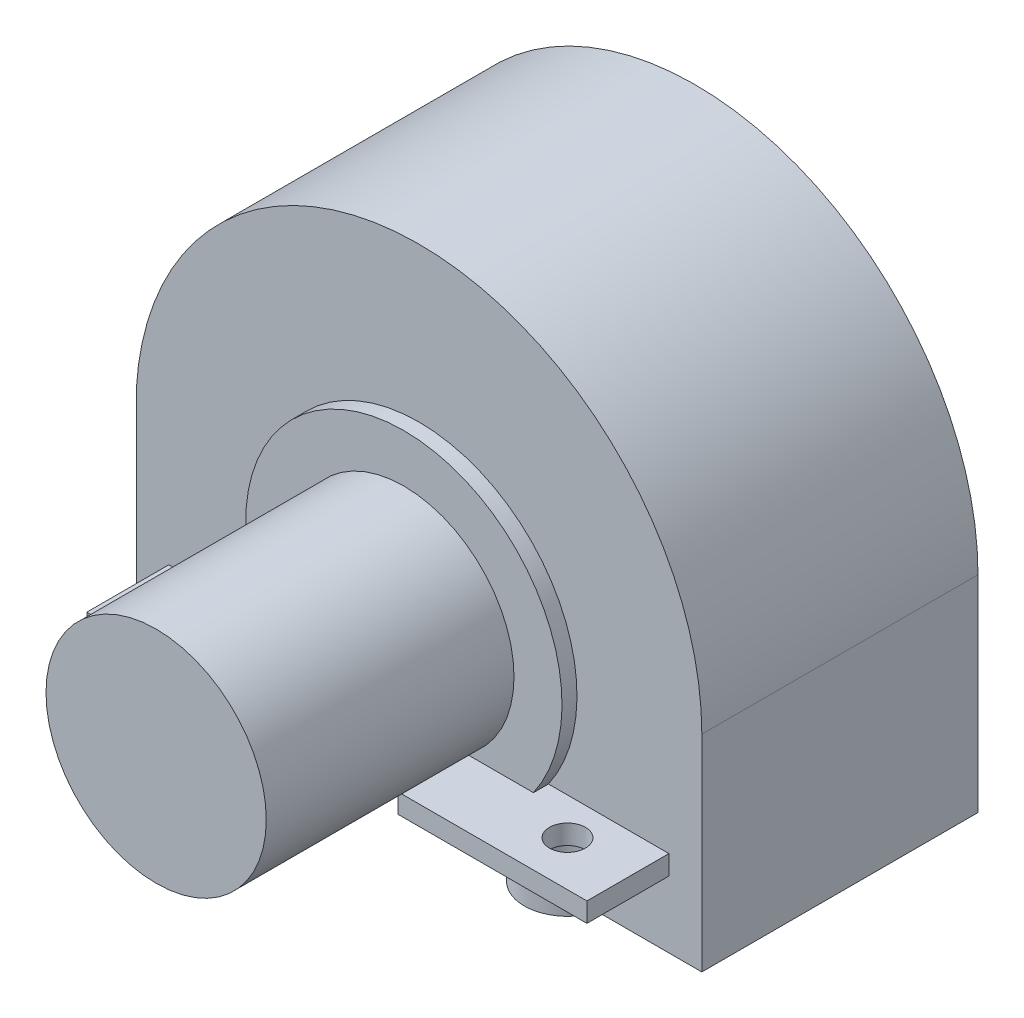
SolidWorks part; units mm, degrees
ref_plane "Front Plane" through (0, 0, 0) normal (0, 0, 1) x (1, 0, 0)
ref_plane "Top Plane" through (0, 0, 0) normal (0, 1, 0) x (1, 0, 0)
ref_plane "Right Plane" through (0, 0, 0) normal (1, 0, 0) x (0, 0, -1)
sketch "Sketch1" plane through (0, 0, 0) normal (0, 0, 1) x (1, 0, 0)
  line L1 (-36.8438, 2.145) -> (36.9062, 2.145)
  line L2 (-36.8438, 2.145) -> (-36.8438, -26.8618)
  line L3 (-36.8438, -26.8618) -> (36.9062, -26.8618)
  line L4 (36.9062, 2.145) -> (36.9062, -26.8618)
  circle A0 centre (0, 0) radius 36.9062
  dimension "D1" = 73.8124
  dimension "D2" = 29.0068
extrude "Boss-Extrude1" add sketch "Sketch1" along normal blind 36.0172 contours L1 A0 | L2 A0 L3 L1 | A0 L3 L4 | A0 L2 L3
sketch "Sketch6" plane through (0, 0, 0) normal (0, 0, -1) x (-1, 0, 0)
  line L0 (-21.1626, -26.8618) -> (21.1626, -26.8618)
  line L1 (0, -3.81) -> (0, 0) construction
  line L2 (36.8438, -26.8618) -> (-36.9062, -26.8618) construction
  circle A0 centre (0, -3.81) radius 31.2928
  line M4 (-36.9062, -26.8618) -> (36.8438, -26.8618)
  dimension "D2" = 62.5856
  dimension "D1" = 3.81
sketch "Sketch7" plane through (0, 0, 36.0172) normal (0, 0, 1) x (1, 0, 0)
  line L0 (0, 0) -> (0, -3.81) construction
  circle A0 centre (0, -3.81) radius 31.2928
  dimension "D2" = 62.5856
  dimension "D1" = 3.81
extrude "Boss-Extrude4" add sketch "Sketch7" against normal blind 36.0172
extrude "Cut-Extrude2" cut sketch "Sketch6" against normal blind 6.35 contours A0 M4
sketch "Sketch9" plane through (0, 0, 36.0172) normal (0, 0, 1) x (1, 0, 0)
  line L0 (-21.1626, -26.8618) -> (21.1626, -26.8618)
  line L1 (0, 0) -> (0, -3.81) construction
  circle A0 centre (0, -3.81) radius 31.2928
  arc M3 (-21.1626, -26.8618) -> (21.1626, -26.8618) centre (0, -3.81) ccw
  dimension "D2" = 62.5856
  dimension "D1" = 3.81
extrude "Cut-Extrude3" cut sketch "Sketch9" against normal blind 10.795 contours L0 M3
sketch "Sketch10" plane through (0, 0, 0) normal (0, 0, -1) x (-1, 0, 0)
  line L0 (0, 0) -> (0, -3.81) construction
  circle A0 centre (0, -3.81) radius 2.8067
  dimension "D2" = 5.6134
  dimension "D1" = 3.81
extrude "Boss-Extrude5" add sketch "Sketch10" along normal blind 5.4864
sketch "Sketch11" plane through (0, 0, 36.0172) normal (0, 0, 1) x (1, 0, 0)
  line L0 (0, 0) -> (0, -3.81) construction
  circle A0 centre (0, -3.81) radius 20.6248
  dimension "D2" = 41.2496
  dimension "D1" = 3.81
extrude "Boss-Extrude6" add sketch "Sketch11" along normal blind 1.9558
sketch "Sketch12" plane through (0, 0, 37.973) normal (0, 0, 1) x (1, 0, 0)
  circle A0 centre (0, -3.81) radius 14.3637
  dimension "D1" = 28.7274
extrude "Boss-Extrude7" add sketch "Sketch12" along normal blind 32.3088
sketch "Sketch13" plane through (0, 0, 36.0172) normal (0, 0, 1) x (1, 0, 0)
  line L0 (0, -18.1737) -> (32.6136, -18.1737) construction
  line L1 (0, -18.1737) -> (-32.6136, -18.1737) construction
  line L3 (32.6136, -18.1737) -> (7.9756, -18.1737)
  line L4 (32.6136, -18.1737) -> (32.6136, -15.6337)
  line L5 (32.6136, -15.6337) -> (7.9756, -15.6337)
  line L6 (7.9756, -18.1737) -> (7.9756, -15.6337)
  line L7 (-32.6136, -18.1737) -> (-7.9756, -18.1737)
  line L8 (-32.6136, -18.1737) -> (-32.6136, -15.6337)
  line L9 (-32.6136, -15.6337) -> (-7.9756, -15.6337)
  line L10 (-7.9756, -18.1737) -> (-7.9756, -15.6337)
  circle A0 centre (0, -3.81) radius 14.3637
  circle M5 centre (0, -3.81) radius 20.6248
  dimension "D1" = 28.7274
  dimension "D2" = 32.6136
  dimension "D3" = 32.6136
  dimension "D4" = 24.638
  dimension "D5" = 24.638
  dimension "D6" = 2.54
  dimension "D7" = 2.54
extrude "Boss-Extrude9" add sketch "Sketch13" along normal blind 10.6934 contours L9 L8 L7 M5 | A0 L9 L7 L10 M5 | A0 L6 L3 L5 M5 | L4 L5 L3 M5
sketch "Sketch14" plane through (0, -15.6337, 0) normal (0, 1, 0) x (1, 0, 0)
  line L0 (-32.6136, -40.8432) -> (-24.2062, -40.8432) construction
  line L2 (-32.6136, -46.7106) -> (-32.6136, -36.0172) construction
  line L4 (-24.2062, -40.8432) -> (-24.2062, -46.7106) construction
  line L5 (-32.6136, -46.7106) -> (-8.1557, -46.7106) construction
  line L7 (32.6136, -40.8432) -> (24.2062, -40.8432) construction
  line L8 (32.6136, -46.7106) -> (32.6136, -36.0172) construction
  line L9 (24.2062, -40.8432) -> (24.2062, -46.7106) construction
  line L10 (32.6136, -46.7106) -> (8.1557, -46.7106) construction
  circle A0 centre (-24.2062, -40.8432) radius 2.3495
  circle A1 centre (24.2062, -40.8432) radius 2.3495
  dimension "D5" = 4.699
  dimension "D6" = 4.699
  dimension "D1" = 8.4074
  dimension "D2" = 5.8674
  dimension "D3" = 8.4074
  dimension "D4" = 5.8674
extrude "Cut-Extrude4" cut sketch "Sketch14" against normal up to surface (2.54 mm away) up to face at (18.4634, -18.1737, 40.2336)
sketch "Sketch15" plane through (0, 0, 0) normal (0, 0, -1) x (-1, 0, 0)
  line L0 (0, -3.81) -> (0, -15.748) construction
  line L1 (0, -15.748) -> (7.366, -15.748) construction
  line L3 (7.366, -15.748) -> (-19.685, -15.748)
  line L4 (7.366, -15.748) -> (7.366, -18.288)
  line L5 (7.366, -18.288) -> (-19.685, -18.288)
  line L6 (-19.685, -15.748) -> (-19.685, -18.288)
  dimension "D1" = 11.938
  dimension "D2" = 7.366
  dimension "D3" = 27.051
  dimension "D4" = 2.54
extrude "Boss-Extrude10" add sketch "Sketch15" along normal blind 11.3538
sketch "Sketch16" plane through (0, -15.748, 0) normal (0, 1, 0) x (1, 0, 0)
  line L0 (5.6985, 11.3538) -> (5.6985, 4.699) construction
  line L1 (-7.366, 11.3538) -> (19.685, 11.3538) construction
  circle A0 centre (5.6985, 4.699) radius 2.3495
  dimension "D2" = 4.699
  dimension "D1" = 6.6548
extrude "Cut-Extrude5" cut sketch "Sketch16" against normal up to surface (2.54 mm away) up to face at (6.1595, -18.288, -5.6769)
sketch "Sketch17" plane through (0, -18.288, 0) normal (0, -1, 0) x (1, 0, 0)
  line L0 (0.0724, -4.699) -> (0, 0)
  line L1 (11.3246, -4.699) -> (11.3246, 0)
  line L2 (19.685, 0) -> (-7.366, 0) construction
  line L3 (11.3246, 0) -> (0, 0)
  arc A0 (0.0724, -4.699) -> (11.3246, -4.699) centre (5.6985, -4.699) ccw
  circle A1 centre (5.6985, -4.699) radius 3.7846
  dimension "D1" = 11.2522
  dimension "D2" = 7.5692
extrude "Boss-Extrude11" add sketch "Sketch17" along normal blind 2.3622
sketch "Sketch18" plane through (0, -18.1737, 0) normal (0, -1, 0) x (1, 0, 0)
  line L0 (-29.8323, 40.8432) -> (-29.8323, 36.0172)
  line L2 (-32.6136, 36.0172) -> (-14.8009, 36.0172) construction
  line L3 (-18.5801, 40.8432) -> (-18.5801, 36.0172)
  line L4 (29.8323, 40.8432) -> (29.8323, 36.0172)
  line L5 (32.6136, 36.0172) -> (14.8009, 36.0172) construction
  line L6 (18.5801, 40.8432) -> (18.5801, 36.0172)
  line L7 (-29.8323, 36.0172) -> (-18.5801, 36.0172)
  arc A0 (29.8323, 40.8432) -> (18.5801, 40.8432) centre (24.2062, 40.8432) ccw
  circle A1 centre (24.2062, 40.8432) radius 3.7846
  circle A2 centre (-24.2062, 40.8432) radius 3.7846
  arc A3 (-18.5801, 40.8432) -> (-29.8323, 40.8432) centre (-24.2062, 40.8432) ccw
  line M5 (14.8009, 36.0172) -> (32.6136, 36.0172)
  dimension "D1" = 11.2522
  dimension "D2" = 7.5692
  dimension "D3" = 7.5692
  dimension "D4" = 11.2522
extrude "Boss-Extrude13" add sketch "Sketch18" along normal blind 2.3622 contours L3 A3 L0 L7 A2 | L4 A0 L6 A1 M5
